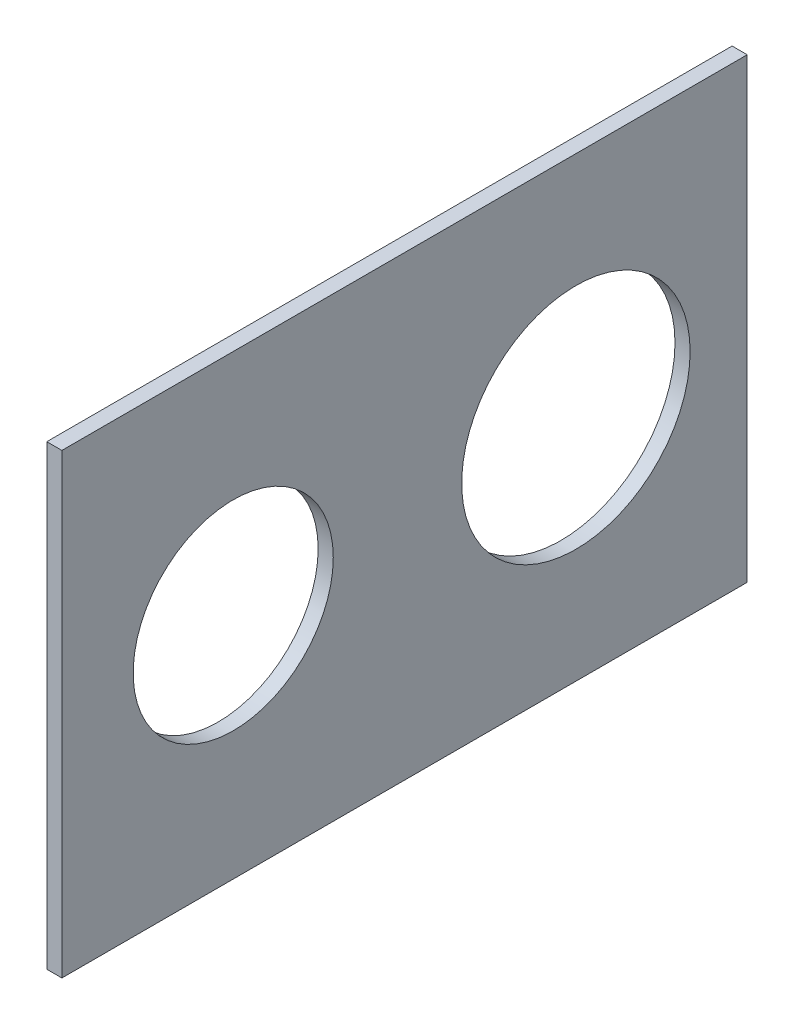
SolidWorks part; units mm, degrees
material "ASTM A36 Steel"
ref_plane "Front Plane" through (0, 0, 0) normal (1, 0, 0) x (0, 1, 0)
ref_plane "Top Plane" through (0, 0, 0) normal (0, 0, 1) x (0, 1, 0)
ref_plane "Right Plane" through (0, 0, 0) normal (0, 1, 0) x (-1, 0, 0)
sketch "Sketch1" plane through (0, 0, 0) normal (1, 0, 0) x (0, 1, 0)
  line L1 (0, 0) -> (50.8, 0)
  line L2 (0, 0) -> (0, 76.2)
  line L3 (0, 76.2) -> (50.8, 76.2)
  line L4 (50.8, 0) -> (50.8, 76.2)
  dimension "D1" = 76.2
  dimension "D2" = 50.8
extrude "Boss-Extrude1" add sketch "Sketch1" along normal blind 1.6812 contours L4 L3 L2 L1
sketch "Sketch3" plane through (1.6812, 0, 0) normal (1, 0, 0) x (0, 1, 0)
  line L0 (0, 76.2) -> (50.8, 76.2) construction
  line L1 (0, 0) -> (50.8, 0) construction
  circle A0 centre (25.4, 57.15) radius 11.1252
  circle A1 centre (25.4, 19.05) radius 12.7
  dimension "D1" = 22.2504
  dimension "D2" = 25.4
  dimension "D3" = 19.05
  dimension "D4" = 19.05
extrude "Cut-Extrude1" cut sketch "Sketch3" against normal through all
equation "\"LOAD\"= 600'Force applied to link (lbf)"
equation "\"LENGTH\"= 3'Length/Height of Link (in)"
equation "\"WIDTH\"= 2'Width of Link (in)"
equation "\"SAFETY_FAC\"= 4'Given safety factor "
equation "\"STRENGTH\"= 36259.4'Yield Strength of A36 Steel (psi)"
equation "\"DIAMETER_A\"= 0.876'Calculated Diameter of Feature A (in)"
equation "\"DIAMETER_1\"= 1'Given Diameter of Link Hole (in)"
equation "\"DIFFERENCE\"= \"WIDTH\" - \"DIAMETER_1\"'Calculated Largest Differnce of Width (in)"
equation "\"LINK_THICK\"= ( \"LOAD\" * \"SAFETY_FAC\" ) / ( \"DIFFERENCE\" * \"STRENGTH\" )'Calculated Thickness of the link (in)"
equation "\"D1@Sketch1\"=\"LENGTH\""
equation "\"D2@Sketch1\"=\"WIDTH\""
equation "\"D1@Boss-Extrude1\"=\"LINK_THICK\""
equation "\"D1@Sketch3\"=\"DIAMETER_A\""
equation "\"D2@Sketch3\"=\"DIAMETER_1\""
equation "\"D3@Sketch3\"=\"LENGTH\"/4"
equation "\"D4@Sketch3\"=\"LENGTH\"/4"
